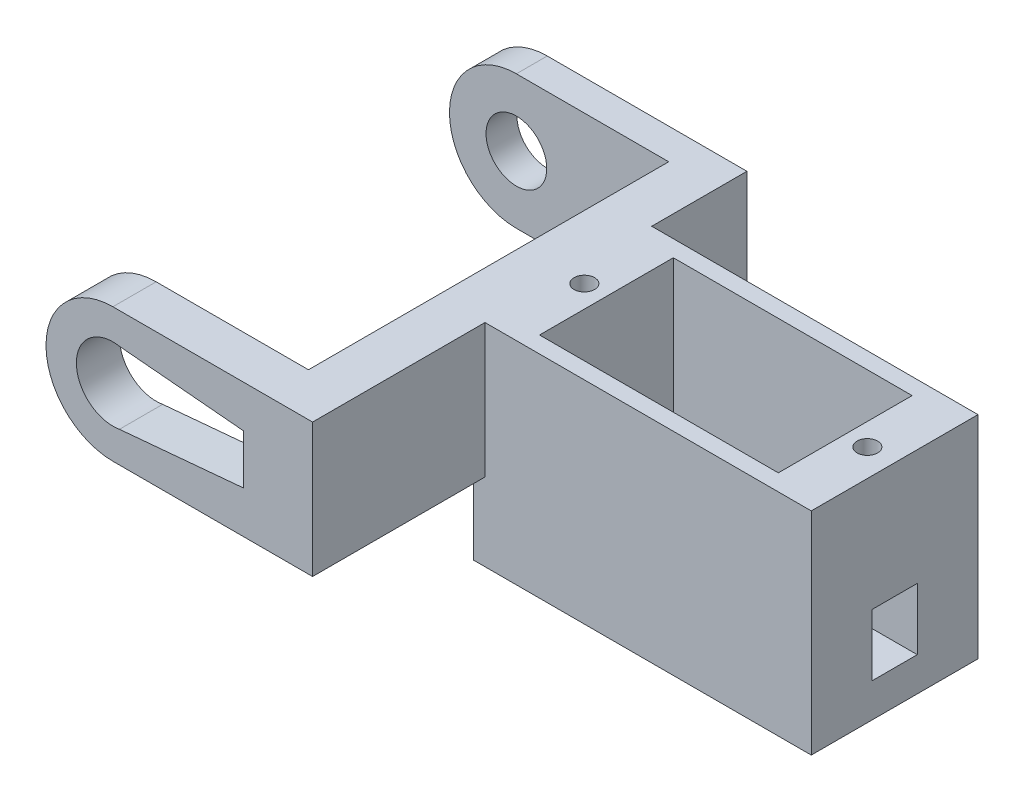
SolidWorks part; units mm, degrees
material "ABS"
ref_plane "Front Plane" through (0, 0, 0) normal (0, 0, 1) x (1, 0, 0)
ref_plane "Top Plane" through (0, 0, 0) normal (0, 1, 0) x (1, 0, 0)
ref_plane "Right Plane" through (0, 0, 0) normal (1, 0, 0) x (0, 0, -1)
sketch "Sketch1" plane through (0, 0, 0) normal (0, 1, 0) x (1, 0, 0)
  line L1 (-41.1, -8.1) -> (-8.3, -8.1)
  line L2 (-41.1, -8.1) -> (-41.1, 8.1)
  line L3 (-41.1, 8.1) -> (-8.3, 8.1)
  line L4 (-8.3, -8.1) -> (-8.3, 8.1)
extrude "Boss-Extrude1" add sketch "Sketch1" along normal mid plane 20.55 from offset 60.725
sketch "Sketch2" plane through (0, 0, 0) normal (1, 0, 0) x (0, 0, -1)
  line L1 (-24.85, 58) -> (17.35, 58)
  line L2 (-24.85, 58) -> (-24.85, 71)
  line L3 (-24.85, 71) -> (17.35, 71)
  line L4 (17.35, 58) -> (17.35, 71)
extrude "Boss-Extrude2" add sketch "Sketch2" along normal mid plane 4.6 from offset 42.3
sketch "Sketch3" plane through (0, 0, 0) normal (0, 0, 1) x (1, 0, 0)
  circle A0 centre (-59.4, 64.5) radius 6.5
extrude "Boss-Extrude3" add sketch "Sketch3" along normal mid plane 4.2 from offset 22.75
sketch "Sketch4" plane through (0, 0, 0) normal (0, 0, 1) x (1, 0, 0)
  line L0 (-40, 71) -> (-44.6, 71) construction
  line L1 (-59.4, 58) -> (-41.1, 58)
  line L2 (-59.4, 58) -> (-59.4, 71)
  line L3 (-59.4, 71) -> (-41.1, 71)
  line L4 (-41.1, 58) -> (-41.1, 71)
  circle A0 centre (-59.4, 64.5) radius 6.5 construction
extrude "Boss-Extrude4" add sketch "Sketch4" along normal mid plane 4.2 from offset 22.75
sketch "Sketch5" plane through (0, 0, 0) normal (0, 0, 1) x (1, 0, 0)
  circle A0 centre (-59.4, 64.5) radius 3.55
extrude "Cut-Extrude1" cut sketch "Sketch5" against normal mid plane 4.2 from offset 22.75
sketch "Sketch6" plane through (0, 0, 0) normal (0, 0, 1) x (1, 0, 0)
  line L0 (-59.4, 60.95) -> (-46.7, 62.0967)
  line L1 (-46.7, 62.0967) -> (-46.7, 66.9033)
  line L2 (-46.7, 66.9033) -> (-59.4, 68.05)
  line L3 (-59.4, 68.05) -> (-59.4, 60.95)
  circle A0 centre (-59.4, 64.5) radius 3.55 construction
extrude "Cut-Extrude2" cut sketch "Sketch6" against normal mid plane 4.2 from offset 22.75
sketch "Sketch7" plane through (0, 0, 0) normal (0, 0, 1) x (1, 0, 0)
  circle A0 centre (-59.4, 64.5) radius 6.5
extrude "Boss-Extrude5" add sketch "Sketch7" along normal mid plane 3 from offset 15.85
sketch "Sketch8" plane through (0, 0, 0) normal (0, 0, 1) x (1, 0, 0)
  line L0 (-40, 71) -> (-59.4, 71) construction
  line L1 (-59.4, 58) -> (-41.1, 58)
  line L2 (-59.4, 58) -> (-59.4, 71)
  line L3 (-59.4, 71) -> (-41.1, 71)
  line L4 (-41.1, 58) -> (-41.1, 71)
extrude "Boss-Extrude6" add sketch "Sketch8" along normal mid plane 3 from offset 15.85
sketch "Sketch9" plane through (0, 0, 0) normal (0, 0, 1) x (1, 0, 0)
  circle A0 centre (-59.4, 64.5) radius 2.95
extrude "Cut-Extrude3" cut sketch "Sketch9" against normal mid plane 3 from offset 15.85
sketch "Sketch10" plane through (0, 0, 0) normal (0, 1, 0) x (1, 0, 0)
  line L1 (-36.3, -6.5) -> (-13.1, -6.5)
  line L2 (-36.3, -6.5) -> (-36.3, 6.5)
  line L3 (-36.3, 6.5) -> (-13.1, 6.5)
  line L4 (-13.1, -6.5) -> (-13.1, 6.5)
extrude "Cut-Extrude4" cut sketch "Sketch10" against normal mid plane 17.25 from offset 62.375
sketch "Sketch11" plane through (0, 0, 0) normal (0, 1, 0) x (1, 0, 0)
  circle A0 centre (-38.45, 0) radius 1
extrude "Cut-Extrude5" cut sketch "Sketch11" against normal mid plane 6 from offset 68
sketch "Sketch12" plane through (0, 0, 0) normal (0, 1, 0) x (1, 0, 0)
  circle A0 centre (-10.95, 0) radius 1
extrude "Cut-Extrude6" cut sketch "Sketch12" against normal mid plane 6 from offset 68
sketch "Sketch13" plane through (0, 0, 0) normal (0, 1, 0) x (1, 0, 0)
  circle A0 centre (-19.2, 0) radius 3.15
extrude "Cut-Extrude7" cut sketch "Sketch13" against normal mid plane 2.6 from offset 51.75
sketch "Sketch14" plane through (0, 0, 0) normal (1, 0, 0) x (0, 0, -1)
  line L1 (-2.2, 53.75) -> (2.2, 53.75)
  line L2 (-2.2, 53.75) -> (-2.2, 59.75)
  line L3 (-2.2, 59.75) -> (2.2, 59.75)
  line L4 (2.2, 53.75) -> (2.2, 59.75)
extrude "Cut-Extrude8" cut sketch "Sketch14" against normal mid plane 4.8 from offset 10.7
